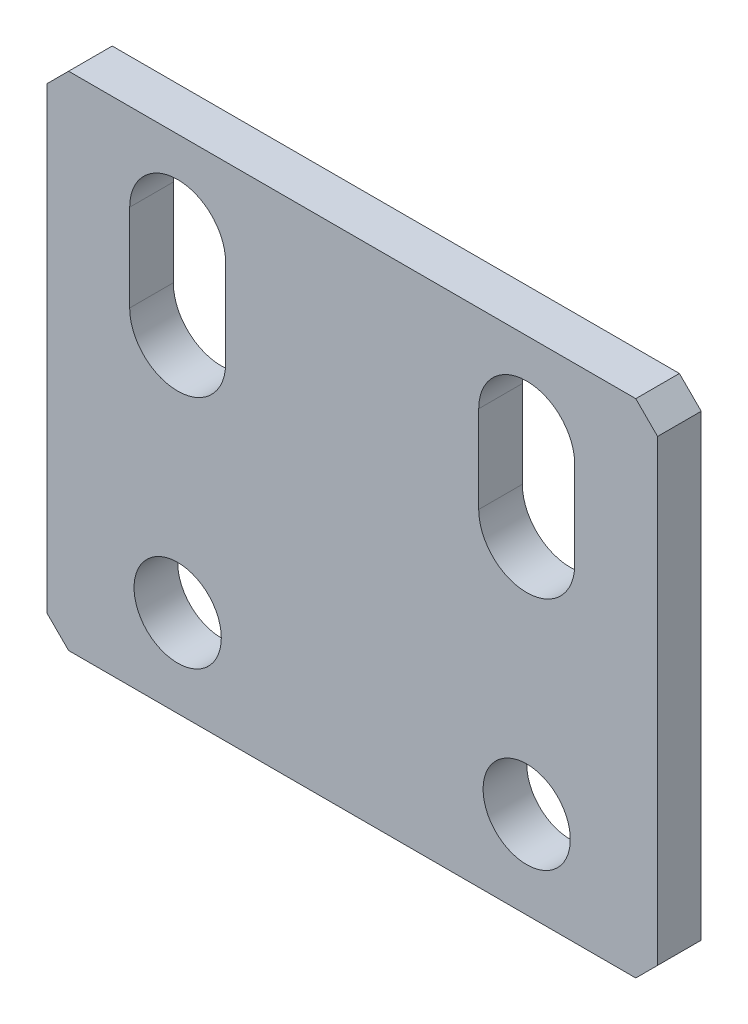
SolidWorks part; units mm, degrees
ref_plane "Front" through (0, 0, 0) normal (0, 0, 1) x (1, 0, 0)
ref_plane "Top" through (0, 0, 0) normal (0, 1, 0) x (1, 0, 0)
ref_plane "Right" through (0, 0, 0) normal (1, 0, 0) x (0, 0, -1)
sketch "Esquisse1" plane through (0, 0, 0) normal (0, 0, 1) x (1, 0, 0)
  line L1 (0, 0) -> (28, 0)
  line L2 (0, 0) -> (0, 23)
  line L3 (0, 23) -> (28, 23)
  line L4 (28, 0) -> (28, 23)
  dimension "D1" = 23
  dimension "D2" = 28
extrude "Boss.-Extru.1" add sketch "Esquisse1" along normal blind 2
sketch "Esquisse2" plane through (0, 0, 2) normal (0, 0, 1) x (1, 0, 0)
  line L0 (6, 19) -> (6, 15) construction
  line L1 (8.2, 19) -> (8.2, 15)
  line L2 (3.8, 19) -> (3.8, 15)
  line L3 (14, 0) -> (14, 23) construction
  line L4 (0, 0) -> (28, 0) construction
  line L5 (28, 23) -> (0, 23) construction
  line L6 (22, 19) -> (22, 15) construction
  line L7 (19.8, 19) -> (19.8, 15)
  line L8 (24.2, 19) -> (24.2, 15)
  line L9 (14, 4) -> (6, 4) construction
  line L10 (6, 4) -> (6, 12.8) construction
  arc A0 (8.2, 19) -> (3.8, 19) centre (6, 19) ccw
  arc A1 (3.8, 15) -> (8.2, 15) centre (6, 15) ccw
  arc A2 (19.8, 19) -> (24.2, 19) centre (22, 19) cw
  arc A3 (24.2, 15) -> (19.8, 15) centre (22, 15) cw
  circle A4 centre (6, 4) radius 2
  circle A5 centre (22, 4) radius 2
  point P2 (6, 17)
  point P15 (22, 17)
  dimension "D3" = 2.2
  dimension "D5" = 4
  dimension "D1" = 16
  dimension "D2" = 4
  dimension "D4" = 17
  dimension "D6" = 4
extrude "Enlèv. mat.-Extru.1" cut sketch "Esquisse2" against normal through all
chamfer "Chanfrein1" distance 1 angle 45 4 edges at (28, 23, 1) (0, 23, 1) (0, 0, 1) (28, 0, 1)
